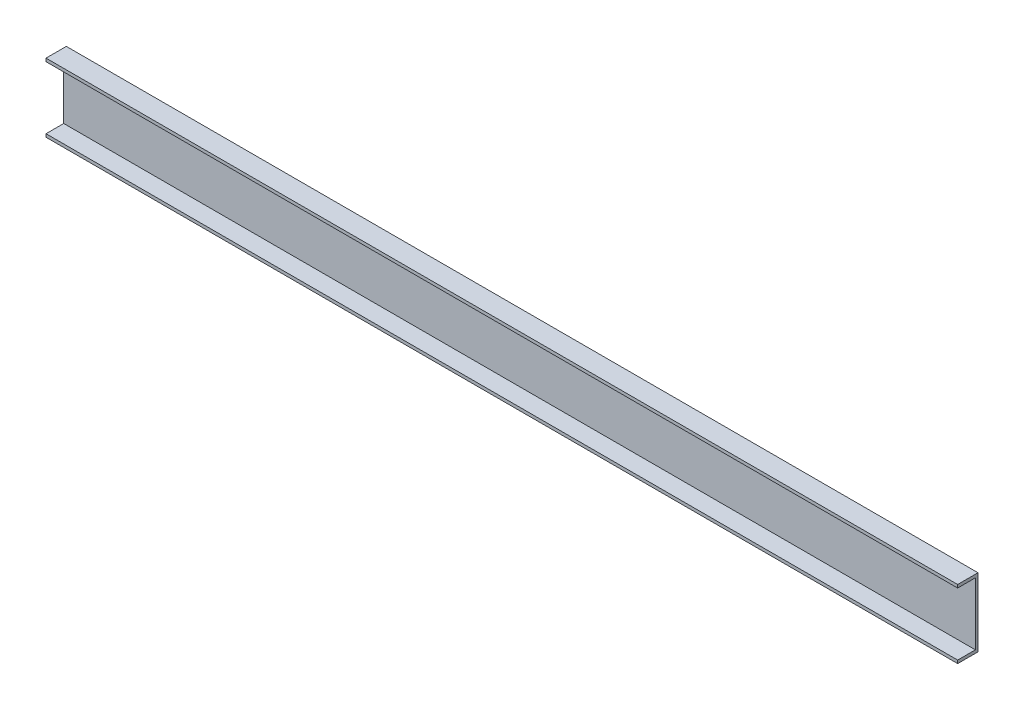
SolidWorks part; units mm, degrees
ref_plane "前视" through (0, 0, 0) normal (0, 0, 1) x (1, 0, 0)
ref_plane "上视" through (0, 0, 0) normal (0, 1, 0) x (1, 0, 0)
ref_plane "右视" through (0, 0, 0) normal (1, 0, 0) x (0, 0, -1)
sketch "草图1" plane through (0, 0, 0) normal (0, 0, 1) x (1, 0, 0)
  line L0 (-253.2778, 0) -> (2143.7198, 0) construction
  line L1 (0, 293.7967) -> (0, -293.7967) construction
  line L2 (1484.3386, 80) -> (1995, 80) construction
  line L3 (-1995, 150) -> (1995, 150)
  line L4 (-1995, 150) -> (-1995, -150)
  line L5 (-1995, -150) -> (1995, -150)
  line L6 (1995, 150) -> (1995, -150)
  line L7 (1940, 137.9179) -> (1940, -34.3032) construction
  line L8 (1860, 137.9179) -> (1860, -34.3032) construction
  line L9 (1780, -27.7215) -> (1780, 137.9179) construction
  line L10 (1700, 137.9179) -> (1700, -27.7215) construction
  line L11 (24.2318, 80) -> (382.2761, 80) construction
  line L12 (60, 137.9179) -> (60, -34.3032) construction
  line L13 (140, -34.3032) -> (140, 137.9179) construction
  circle A0 centre (1940, 0) radius 13
  circle A1 centre (1860, 0) radius 13
  circle A2 centre (1780, 0) radius 13
  circle A3 centre (1700, 0) radius 13
  circle A4 centre (1700, 80) radius 13
  circle A5 centre (1780, 80) radius 13
  circle A6 centre (1860, 80) radius 13
  circle A7 centre (1940, 80) radius 13
  circle A8 centre (1940, -80) radius 13
  circle A9 centre (1860, -80) radius 13
  circle A10 centre (1780, -80) radius 13
  circle A11 centre (1700, -80) radius 13
  circle A12 centre (-1700, -80) radius 13
  circle A13 centre (-1780, -80) radius 13
  circle A14 centre (-1860, -80) radius 13
  circle A15 centre (-1940, -80) radius 13
  circle A16 centre (-1940, 80) radius 13
  circle A17 centre (-1860, 80) radius 13
  circle A18 centre (-1780, 80) radius 13
  circle A19 centre (-1700, 80) radius 13
  circle A20 centre (-1700, 0) radius 13
  circle A21 centre (-1780, 0) radius 13
  circle A22 centre (-1860, 0) radius 13
  circle A23 centre (-1940, 0) radius 13
  circle A24 centre (60, 80) radius 13
  circle A25 centre (140, 80) radius 13
  circle A28 centre (140, -80) radius 13
  circle A29 centre (60, -80) radius 13
  circle A30 centre (-60, -80) radius 13
  circle A31 centre (-140, -80) radius 13
  circle A34 centre (-140, 80) radius 13
  circle A35 centre (-60, 80) radius 13
  dimension "D8" = 26
  dimension "D11" = 26
  dimension "D1" = 300
  dimension "D2" = 3990
  dimension "D3" = 80
  dimension "D4" = 55
  dimension "D5" = 80
  dimension "D6" = 80
  dimension "D7" = 80
  dimension "D9" = 60
  dimension "D10" = 80
extrude "基体-拉伸" add sketch "草图1" along normal blind 11.5
sketch "草图2" plane through (0, 0, 11.5) normal (0, 0, 1) x (1, 0, 0)
  line L0 (1995, -150) -> (1995, 150) construction
  line L1 (-1995, 150) -> (1995, 150)
  line L2 (-1995, 150) -> (-1995, 136.5)
  line L3 (-1995, 136.5) -> (1995, 136.5)
  line L4 (1995, 150) -> (1995, 136.5)
  line L5 (-335.9089, 0) -> (412.8346, 0) construction
  line L6 (1995, -150) -> (1995, -136.5)
  line L7 (-1995, -136.5) -> (1995, -136.5)
  line L8 (-1995, -150) -> (-1995, -136.5)
  line L9 (-1995, -150) -> (1995, -150)
  dimension "D1" = 13.5
extrude "凸台-拉伸1" add sketch "草图2" along normal blind 77.5
sketch "草图3" plane through (0, 0, 0) normal (0, 0, -1) x (-1, 0, 0)
  line L0 (-1674.4159, 0) -> (305.1386, 0) construction
  line L1 (0, 210.2636) -> (0, -302.5744) construction
  line L2 (-1995, -150) -> (-1995, 150) construction
  line L3 (-1335, 115) -> (-1265, 115)
  line L4 (-1335, 115) -> (-1335, -115)
  line L5 (-1335, -115) -> (-1265, -115)
  line L6 (-1265, 115) -> (-1265, -115)
  line L7 (-935, 115) -> (-865, 115)
  line L8 (-935, 115) -> (-935, -115)
  line L9 (-935, -115) -> (-865, -115)
  line L10 (-865, 115) -> (-865, -115)
  line L11 (-535, 115) -> (-465, 115)
  line L12 (-535, 115) -> (-535, -115)
  line L13 (-535, -115) -> (-465, -115)
  line L14 (-465, 115) -> (-465, -115)
  line L15 (465, 115) -> (465, -115)
  line L16 (535, -115) -> (465, -115)
  line L17 (535, 115) -> (535, -115)
  line L18 (535, 115) -> (465, 115)
  line L19 (865, 115) -> (865, -115)
  line L20 (935, -115) -> (865, -115)
  line L21 (935, 115) -> (935, -115)
  line L22 (935, 115) -> (865, 115)
  line L23 (1265, 115) -> (1265, -115)
  line L24 (1335, -115) -> (1265, -115)
  line L25 (1335, 115) -> (1335, -115)
  line L26 (1335, 115) -> (1265, 115)
  dimension "D1" = 70
  dimension "D2" = 70
  dimension "D3" = 70
  dimension "D4" = 230
  dimension "D5" = 660
  dimension "D6" = 400
  dimension "D7" = 400
extrude "凸台-拉伸2" add sketch "草图3" along normal blind 16
sketch "草图4" plane through (0, 0, -16) normal (0, 0, -1) x (-1, 0, 0)
  line L0 (0, 492.3244) -> (0, -548.7366) construction
  line L1 (-500, 124.929) -> (-500, -60.2993) construction
  line L2 (-1300, 124.929) -> (-1300, -60.2993) construction
  line L3 (-900, -60.2993) -> (-900, 236.5151) construction
  line L5 (-1594.4016, 80) -> (-322.6426, 80) construction
  line L6 (-1995, -150) -> (-1995, 150) construction
  line L7 (0, 0) -> (-1594.4016, 0) construction
  circle A0 centre (-1300, 0) radius 13
  circle A1 centre (-1300, 80) radius 13
  circle A2 centre (-900, 80) radius 13
  circle A3 centre (-900, 0) radius 13
  circle A4 centre (-500, 80) radius 13
  circle A5 centre (-500, 0) radius 13
  circle A6 centre (-500, -80) radius 13
  circle A7 centre (-900, -80) radius 13
  circle A8 centre (-1300, -80) radius 13
  circle A9 centre (1300, -80) radius 13
  circle A10 centre (900, -80) radius 13
  circle A11 centre (500, -80) radius 13
  circle A12 centre (500, 0) radius 13
  circle A13 centre (500, 80) radius 13
  circle A14 centre (900, 0) radius 13
  circle A15 centre (900, 80) radius 13
  circle A16 centre (1300, 80) radius 13
  circle A17 centre (1300, 0) radius 13
  dimension "D5" = 26
  dimension "D1" = 695
  dimension "D2" = 400
  dimension "D3" = 400
  dimension "D4" = 80
extrude "切除-拉伸1" cut sketch "草图4" against normal through all
sketch "草图5" plane through (0, 0, 11.5) normal (0, 0, 1) x (1, 0, 0)
  line L1 (-1995, 136.5) -> (1995, 136.5)
  line L2 (-1995, 136.5) -> (-1995, -136.5)
  line L3 (-1995, -136.5) -> (1995, -136.5)
  line L4 (1995, 136.5) -> (1995, -136.5)
extrude "凸台-拉伸3" add sketch "草图5" against normal blind 11.5
sketch "草图6" plane through (0, 0, 0) normal (0, 0, -1) x (-1, 0, 0)
  line L1 (-1335, 115) -> (-1265, 115)
  line L2 (-1335, 115) -> (-1335, -115)
  line L3 (-1335, -115) -> (-1265, -115)
  line L4 (-1265, 115) -> (-1265, -115)
  line L5 (-935, 115) -> (-865, 115)
  line L6 (-935, 115) -> (-935, -115)
  line L7 (-935, -115) -> (-865, -115)
  line L8 (-865, 115) -> (-865, -115)
  line L9 (-535, 115) -> (-465, 115)
  line L10 (-535, 115) -> (-535, -115)
  line L11 (-535, -115) -> (-465, -115)
  line L12 (-465, 115) -> (-465, -115)
  line L13 (465, 115) -> (535, 115)
  line L14 (465, 115) -> (465, -115)
  line L15 (465, -115) -> (535, -115)
  line L16 (535, 115) -> (535, -115)
  line L17 (865, 115) -> (935, 115)
  line L18 (865, 115) -> (865, -115)
  line L19 (865, -115) -> (935, -115)
  line L20 (935, 115) -> (935, -115)
  line L21 (1265, 115) -> (1335, 115)
  line L22 (1265, 115) -> (1265, -115)
  line L23 (1265, -115) -> (1335, -115)
  line L24 (1335, 115) -> (1335, -115)
extrude "凸台-拉伸4" add sketch "草图6" along normal blind 16
